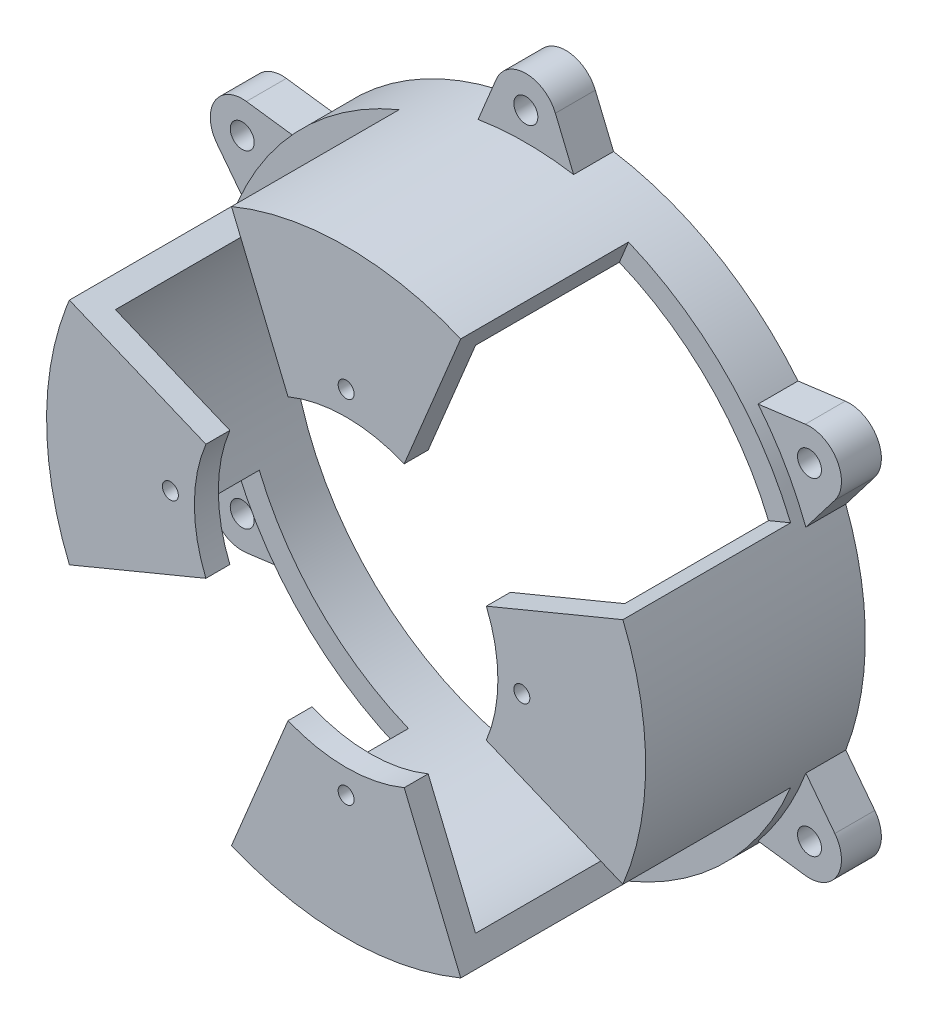
SolidWorks part; units mm, degrees
ref_plane "Спереди" through (0, 0, 0) normal (0, 0, 1) x (1, 0, 0)
ref_plane "Сверху" through (0, 0, 0) normal (0, 1, 0) x (1, 0, 0)
ref_plane "Справа" through (0, 0, 0) normal (1, 0, 0) x (0, 0, -1)
sketch "Эскиз1" plane through (0, 0, 0) normal (0, 0, 1) x (1, 0, 0)
  circle A0 centre (0, 0) radius 37.5
  circle A1 centre (0, 0) radius 34.5
  dimension "D1" = 75
  dimension "D2" = 3
extrude "Бобышка-Вытянуть1" add sketch "Эскиз1" along normal blind 24.5
sketch "Эскиз2" plane through (0, 0, 0) normal (0, 0, -1) x (-1, 0, 0)
  line L0 (-3.6955, 42.5307) -> (-5.978, 37.0205)
  line L1 (0, 41) -> (0, 37.5) construction
  line L2 (3.6955, 42.5307) -> (5.978, 37.0205)
  circle A0 centre (0, 41) radius 1.5
  arc A1 (3.6955, 42.5307) -> (-3.6955, 42.5307) centre (0, 41) ccw
  circle A2 centre (0, 0) radius 37.5 construction
  arc A3 (-5.978, 37.0205) -> (5.978, 37.0205) centre (0, 0) cw
  point P10 (0, 0)
  dimension "D1" = 3
  dimension "D2" = 8
  dimension "D4" = 41
  dimension "D3" = 45
extrude "Бобышка-Вытянуть2" add sketch "Эскиз2" against normal blind 5
pattern_circular "Круговой массив1" count 6 over 360 about axis through (0, 0, 0) along (0, 0, 1) of "Бобышка-Вытянуть2"
sketch "Эскиз3" plane through (0, 0, 24.5) normal (0, 0, 1) x (1, 0, 0)
  circle A0 centre (0, 0) radius 37.5
  circle A1 centre (0, 0) radius 19
  circle A2 centre (0, 0) radius 37.5 construction
  dimension "D1" = 38
extrude "Бобышка-Вытянуть3" add sketch "Эскиз3" along normal blind 3
sketch "Эскиз4" plane through (0, 0, 27.5) normal (0, 0, 1) x (1, 0, 0)
  circle A0 centre (22, 0) radius 1
  circle A1 centre (0, -22) radius 1
  circle A2 centre (-22, 0) radius 1
  circle A3 centre (0, 22) radius 1
  point P2 (0, 0)
  point P11 (0, 0)
  dimension "D1" = 2
  dimension "D3" = 44
  dimension "D2" = 4
extrude "Вырез-Вытянуть1" cut sketch "Эскиз4" against normal blind 3
sketch "Эскиз5" plane through (0, 0, 27.5) normal (0, 0, 1) x (1, 0, 0)
  line L0 (0, 0) -> (37.5, 0) construction
  line L1 (0, 0) -> (26.5165, 26.5165) construction
  line L2 (0, 0) -> (34.6455, 14.3506)
  line L3 (0, 0) -> (14.3506, 34.6455)
  circle A0 centre (0, 0) radius 37.5 construction
  arc A1 (14.3506, 34.6455) -> (34.6455, 14.3506) centre (0, 0) cw
  dimension "D2" = 45
  dimension "D1" = 45
extrude "Вырез-Вытянуть2" cut sketch "Эскиз5" against normal blind 21
pattern_circular "Круговой массив2" count 4 over 360 about axis through (0, 0, 24.5) along (0, 0, -1) of "Вырез-Вытянуть2"
